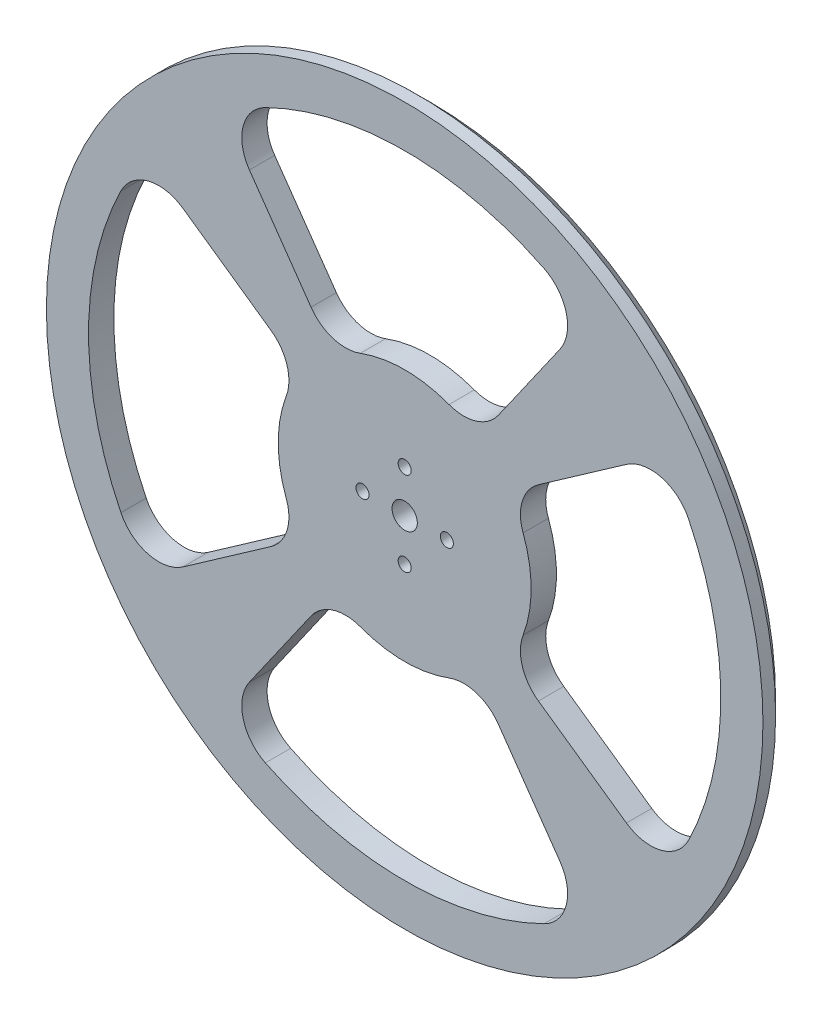
SolidWorks part; units mm, degrees
ref_plane "前视基准面" through (0, 0, 0) normal (0, 0, 1) x (1, 0, 0)
ref_plane "上视基准面" through (0, 0, 0) normal (0, 1, 0) x (1, 0, 0)
ref_plane "右视基准面" through (0, 0, 0) normal (1, 0, 0) x (0, 0, -1)
other "Configuration Table"
sketch "草图1" plane through (0, 0, 0) normal (0, 0, 1) x (1, 0, 0)
  line L0 (0, 0) -> (-10.0376, 14.3352)
  line L1 (0, 0) -> (10.0376, 14.3352)
  line L2 (0, 75) -> (0, 0) construction
  line L3 (28.0994, 40.1301) -> (36.8386, 52.611)
  line L4 (-28.0994, 40.1301) -> (-36.8386, 52.611)
  line L5 (40.1301, 28.0994) -> (52.611, 36.8386)
  line L6 (40.1301, -28.0994) -> (52.611, -36.8386)
  line L7 (28.0994, -40.1301) -> (36.8386, -52.611)
  line L8 (-28.0994, -40.1301) -> (-36.8386, -52.611)
  line L9 (-40.1301, -28.0994) -> (-52.611, -36.8386)
  line L10 (-40.1301, 28.0994) -> (-52.611, 36.8386)
  line L11 (-28.0994, 40.1301) -> (-22.2145, 31.7256)
  line L12 (28.0994, 40.1301) -> (22.2145, 31.7256)
  line L13 (-10.0376, 14.3352) -> (0, 0)
  line L14 (10.0376, 14.3352) -> (0, 0)
  line L15 (40.1301, -28.0994) -> (52.611, -36.8386)
  line L16 (40.1301, -28.0994) -> (31.7256, -22.2145)
  line L17 (40.1301, 28.0994) -> (31.7256, 22.2145)
  line L18 (40.1301, 28.0994) -> (52.611, 36.8386)
  line L19 (-28.0994, -40.1301) -> (-36.8386, -52.611)
  line L20 (-28.0994, -40.1301) -> (-22.2145, -31.7256)
  line L21 (28.0994, -40.1301) -> (22.2145, -31.7256)
  line L22 (28.0994, -40.1301) -> (36.8386, -52.611)
  line L23 (-40.1301, 28.0994) -> (-52.611, 36.8386)
  line L24 (-40.1301, 28.0994) -> (-31.7256, 22.2145)
  line L25 (-40.1301, -28.0994) -> (-31.7256, -22.2145)
  line L26 (-40.1301, -28.0994) -> (-52.611, -36.8386)
  circle A0 centre (0, 0) radius 85
  arc A1 (33.0543, 67.3232) -> (-33.0543, 67.3232) centre (0, 0) ccw
  circle A3 centre (0, 0) radius 17.5
  arc A4 (36.8386, 52.611) -> (33.0543, 67.3232) centre (28.6471, 58.3468) ccw
  arc A7 (-33.0543, 67.3232) -> (-36.8386, 52.611) centre (-28.6471, 58.3468) ccw
  circle A8 centre (0, 0) radius 3
  arc A12 (67.3232, 33.0543) -> (52.611, 36.8386) centre (58.3468, 28.6471) ccw
  arc A13 (67.3232, -33.0543) -> (67.3232, 33.0543) centre (0, 0) ccw
  arc A14 (52.611, -36.8386) -> (67.3232, -33.0543) centre (58.3468, -28.6471) ccw
  arc A18 (33.0543, -67.3232) -> (36.8386, -52.611) centre (28.6471, -58.3468) ccw
  arc A19 (-33.0543, -67.3232) -> (33.0543, -67.3232) centre (0, 0) ccw
  arc A20 (-36.8386, -52.611) -> (-33.0543, -67.3232) centre (-28.6471, -58.3468) ccw
  arc A24 (-67.3232, -33.0543) -> (-52.611, -36.8386) centre (-58.3468, -28.6471) ccw
  arc A25 (-67.3232, 33.0543) -> (-67.3232, -33.0543) centre (0, 0) ccw
  arc A26 (-52.611, 36.8386) -> (-67.3232, 33.0543) centre (-58.3468, 28.6471) ccw
  arc A27 (10.5172, 28.096) -> (-10.5172, 28.096) centre (0, 0) ccw
  arc A28 (10.5172, 28.096) -> (22.2145, 31.7256) centre (14.023, 37.4614) ccw
  arc A29 (-10.5172, 28.096) -> (-22.2145, 31.7256) centre (-14.023, 37.4614) cw
  arc A30 (67.3232, -33.0543) -> (67.3232, 33.0543) centre (0, 0) ccw
  arc A31 (52.611, -36.8386) -> (67.3232, -33.0543) centre (58.3468, -28.6471) ccw
  arc A32 (28.096, -10.5172) -> (31.7256, -22.2145) centre (37.4614, -14.023) ccw
  arc A33 (28.096, -10.5172) -> (28.096, 10.5172) centre (0, 0) ccw
  arc A34 (28.096, 10.5172) -> (31.7256, 22.2145) centre (37.4614, 14.023) cw
  arc A35 (67.3232, 33.0543) -> (52.611, 36.8386) centre (58.3468, 28.6471) ccw
  arc A36 (-33.0543, -67.3232) -> (33.0543, -67.3232) centre (0, 0) ccw
  arc A37 (-36.8386, -52.611) -> (-33.0543, -67.3232) centre (-28.6471, -58.3468) ccw
  arc A38 (-10.5172, -28.096) -> (-22.2145, -31.7256) centre (-14.023, -37.4614) ccw
  arc A39 (-10.5172, -28.096) -> (10.5172, -28.096) centre (0, 0) ccw
  arc A40 (10.5172, -28.096) -> (22.2145, -31.7256) centre (14.023, -37.4614) cw
  arc A41 (33.0543, -67.3232) -> (36.8386, -52.611) centre (28.6471, -58.3468) ccw
  arc A42 (-67.3232, 33.0543) -> (-67.3232, -33.0543) centre (0, 0) ccw
  arc A43 (-52.611, 36.8386) -> (-67.3232, 33.0543) centre (-58.3468, 28.6471) ccw
  arc A44 (-28.096, 10.5172) -> (-31.7256, 22.2145) centre (-37.4614, 14.023) ccw
  arc A45 (-28.096, 10.5172) -> (-28.096, -10.5172) centre (0, 0) ccw
  arc A46 (-28.096, -10.5172) -> (-31.7256, -22.2145) centre (-37.4614, -14.023) cw
  arc A47 (-67.3232, -33.0543) -> (-52.611, -36.8386) centre (-58.3468, -28.6471) ccw
  point P21 (-43.0182, 61.4364)
  point P60 (0, 0)
  point P105 (0, 0)
  dimension "D1" = 170
  dimension "D2" = 150
  dimension "D3" = 10
  dimension "D4" = 35
  dimension "D7" = 10
  dimension "D8" = 6
  dimension "D10" = 60
  dimension "D11" = 10
  dimension "D5" = 35
  dimension "D6" = 35
  dimension "D9" = 4
  dimension "D12" = 4
extrude "凸台-拉伸1" add sketch "草图1" along normal blind 6
sketch "草图2" plane through (0, 0, 6) normal (0, 0, 1) x (1, 0, 0)
  line L0 (0, 0) -> (0, 8.0053) construction
  circle A0 centre (0, 0) radius 10 construction
  circle A1 centre (0, 10) radius 1.55
  dimension "D1" = 20
  dimension "D2" = 3.1
extrude "切除-拉伸1" cut sketch "草图2" against normal through all
pattern_circular "阵列(圆周)2" count 4 over 360 about axis through (0, 0, 0) along (0, 0, 1) of "切除-拉伸1"
chamfer "倒角1" distance 3 angle 45 1 edges at (85, 0, 0)
